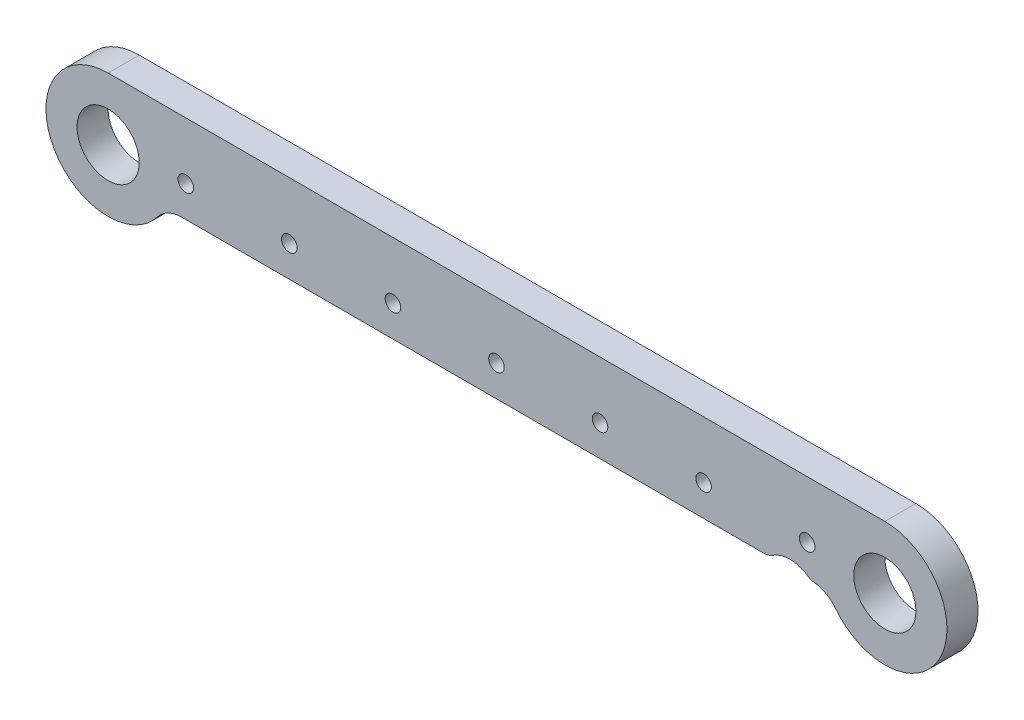
SolidWorks part; units mm, degrees
material "Thornel Mat VMA"
ref_plane "前视基准面" through (0, 0, 0) normal (0, 0, 1) x (1, 0, 0)
ref_plane "上视基准面" through (0, 0, 0) normal (0, 1, 0) x (1, 0, 0)
ref_plane "右视基准面" through (0, 0, 0) normal (1, 0, 0) x (0, 0, -1)
other "Configuration Table"
sketch "草图1" plane through (0, 0, 0) normal (0, 0, 1) x (1, 0, 0)
  line L0 (0, 0) -> (150, 0) construction
  line L1 (0, 12) -> (150, 12)
  line L2 (0, -12) -> (150, -12)
  arc A0 (0, 12) -> (0, -12) centre (0, 0) ccw
  arc A1 (150, -12) -> (150, 12) centre (150, 0) ccw
  circle A2 centre (0, 0) radius 6
  circle A3 centre (150, 0) radius 6
  point P3 (75, 0)
  dimension "D1" = 12
  dimension "D3" = 12
  dimension "D2" = 150
extrude "凸台-拉伸1" add sketch "草图1" along normal blind 6
sketch "草图2" plane through (0, 0, 6) normal (0, 0, 1) x (1, 0, 0)
  line L0 (0, -12) -> (150, -12)
  line L1 (139.0913, -5) -> (10.9087, -5)
  circle A0 centre (0, 0) radius 12
  circle A1 centre (150, 0) radius 12
  line M5 (0, -12) -> (150, -12)
  dimension "D1" = 7
extrude "切除-拉伸1" cut sketch "草图2" against normal blind 6 contours A1 L1 A0 M5
fillet "圆角1" radius 6 2 edges at (139.0913, -5, 3) (10.9087, -5, 3)
sketch "草图6" plane through (0, 0, 6) normal (0, 0, 1) x (1, 0, 0)
  line L0 (15, 1) -> (35, 1) construction
  line L1 (135.7522, -5) -> (14.2478, -5) construction
  circle A0 centre (15, 1) radius 1.5
  circle A1 centre (35, 1) radius 1.5
  circle A2 centre (55, 1) radius 1.5
  circle A3 centre (75, 1) radius 1.5
  circle A4 centre (95, 1) radius 1.5
  circle A5 centre (115, 1) radius 1.5
  circle A6 centre (135, 1) radius 1.5
  dimension "D4" = 3
  dimension "D6" = 20
  dimension "D1" = 20
  dimension "D2" = 6
  dimension "D3" = 15
  dimension "D5" = 6
extrude "切除-拉伸2" cut sketch "草图6" against normal blind 10
sketch "草图7" plane through (0, 0, 0) normal (0, 0, -1) x (-1, 0, 0)
  line L0 (-150, 0) -> (-135.007, -13.2367) construction
  line L1 (-135.007, -13.2367) -> (-131.6942, -9.4843) construction
  line L2 (-150, 0) -> (-150, 33.8252) construction
  circle A0 centre (-131.6942, -9.4843) radius 6
  dimension "D4" = 12
  dimension "D1" = 20
  dimension "D2" = 5.0056
  dimension "D3" = 131.44
extrude "切除-拉伸3" cut sketch "草图7" against normal blind 10
fillet "圆角2" radius 3 2 edges at (127.7078, -5, 3) (135.6805, -5, 3)
